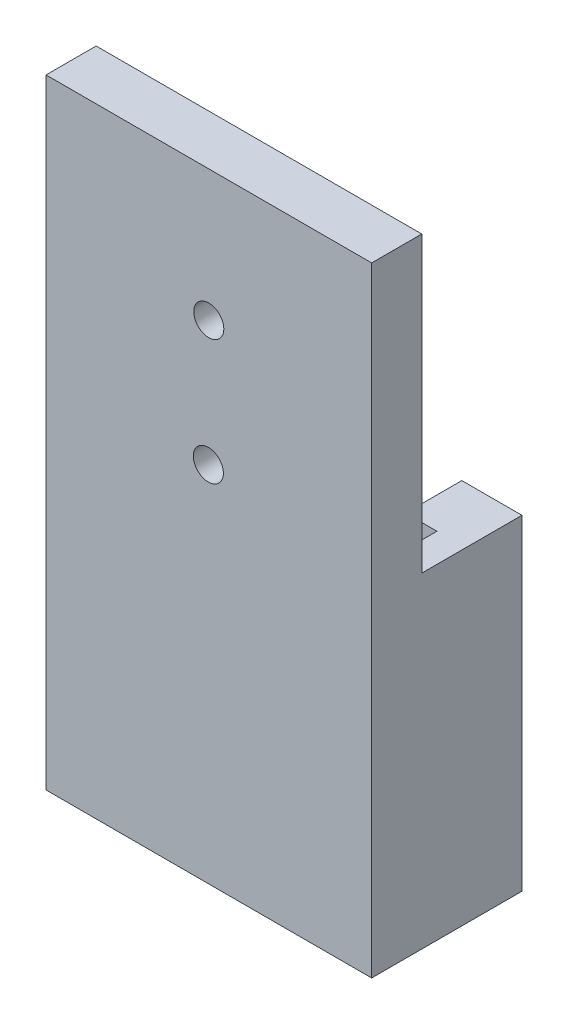
SolidWorks part; units mm, degrees
ref_plane "Plan de face" through (0, 0, 0) normal (0, 0, 1) x (1, 0, 0)
ref_plane "Plan de dessus" through (0, 0, 0) normal (0, 1, 0) x (1, 0, 0)
ref_plane "Plan de droite" through (0, 0, 0) normal (1, 0, 0) x (0, 0, -1)
sketch "Esquisse1" plane through (0, 0, 0) normal (0, 0, 1) x (1, 0, 0)
  line L1 (0, 0) -> (15.7127, 0)
  line L2 (0, 0) -> (0, 32.5724)
  line L3 (0, 32.5724) -> (15.7127, 32.5724)
  line L4 (15.7127, 0) -> (15.7127, 32.5724)
  line L5 (7.8563, 32.5724) -> (7.8563, 0) construction
  circle A0 centre (7.85, 28.9782) radius 1.2
  circle A1 centre (7.8149, 18.9783) radius 1.2
extrude "Boss.-Extru.1" add sketch "Esquisse1" along normal blind 4
sketch "Esquisse2" plane through (0, 0, 0) normal (0, -1, 0) x (1, 0, 0)
  line L0 (-5.1437, 4) -> (20.8563, 4)
  line L1 (-32.7121, 4) -> (48.1874, 4) construction
  line L2 (20.8563, 4) -> (20.8563, -8)
  line L3 (20.8563, -8) -> (16.0563, -8)
  line L4 (7.8563, 4) -> (7.8563, -1.1645) construction
  line L5 (15.7127, 0) -> (0, 0)
  line L6 (0, 0) -> (15.7127, 0) construction
  line L8 (0, 4) -> (15.7127, 4) construction
  line L10 (7.8563, 4) -> (7.8563, 0) construction
  line L11 (-5.1437, 4) -> (-5.1437, -8)
  line L12 (-5.1437, -8) -> (-0.3437, -8)
  line L13 (-0.3437, -3.5) -> (-0.3437, -8)
  line L14 (16.0563, -3.5) -> (18.5676, -3.5)
  line L15 (18.5676, -3.5) -> (18.5676, -0.5)
  line L16 (18.5676, -0.5) -> (15.7134, -0.5)
  line L17 (15.7134, -0.5) -> (15.7127, 0)
  line L18 (16.0563, -3.5) -> (16.0563, -8)
  line L19 (-0.3437, -3.5) -> (-2.855, -3.5)
  line L20 (-2.855, -3.5) -> (-2.855, -0.5)
  line L21 (-2.855, -0.5) -> (-0.0007, -0.5)
  line L22 (-0.0007, -0.5) -> (0, 0)
  dimension "D1" = 4.8
  dimension "D2" = 26
  dimension "D3" = 4.5
  dimension "D4" = 3
extrude "Boss.-Extru.2" add sketch "Esquisse2" along normal blind 10 and the other way blind 16
sketch "Esquisse4" plane through (0, 0, 4) normal (0, 0, 1) x (1, 0, 0)
  line L0 (0, 16) -> (-5.1437, 16)
  line L1 (-5.1437, 16) -> (-5.1437, 39.453)
  line L2 (15.7127, 16) -> (20.8563, 16)
  line L3 (20.8563, 16) -> (20.8563, 39.453)
  line L4 (20.8563, 39.453) -> (-5.1437, 39.453)
  line L5 (0, 16) -> (1.5521, 16)
  line L6 (1.5521, 16) -> (1.5521, 31.4463)
  line L7 (1.5521, 31.4463) -> (14.3444, 31.4463)
  line L8 (14.3444, 31.4463) -> (14.3444, 16)
  line L9 (14.3444, 16) -> (15.7127, 16)
extrude "Boss.-Extru.4" add sketch "Esquisse4" against normal blind 4
